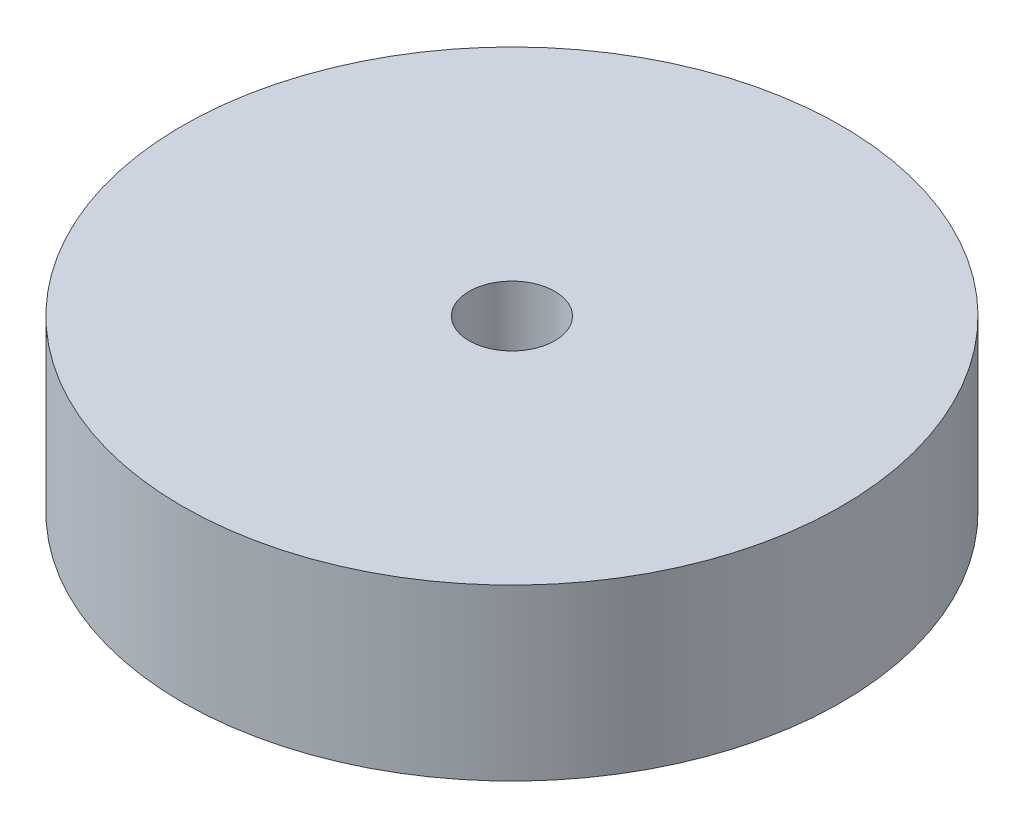
SolidWorks part; units mm, degrees
ref_plane "Front Plane" through (0, 0, 0) normal (0, 0, 1) x (1, 0, 0)
ref_plane "Top Plane" through (0, 0, 0) normal (0, 1, 0) x (1, 0, 0)
ref_plane "Right Plane" through (0, 0, 0) normal (1, 0, 0) x (0, 0, -1)
sketch "Sketch1" plane through (0, 0, 0) normal (0, 1, 0) x (1, 0, 0)
  circle A0 centre (0, 0) radius 200
  circle A1 centre (0, 0) radius 26
  dimension "D1" = 400
  dimension "D2" = 52
extrude "Boss-Extrude1" add sketch "Sketch1" along normal blind 103
